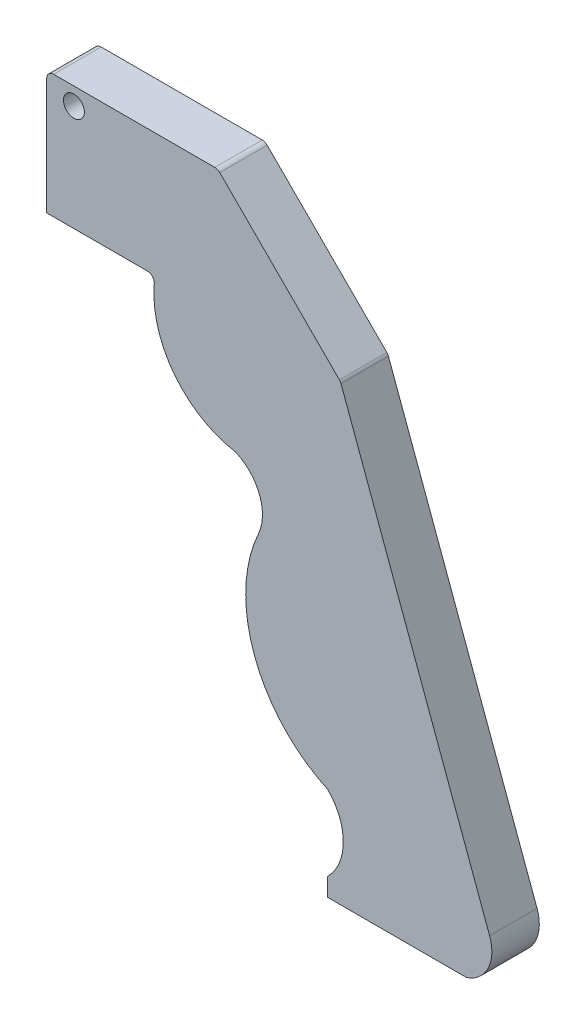
SolidWorks part; units mm, degrees
ref_plane "Front Plane" through (0, 0, 0) normal (0, 0, 1) x (1, 0, 0)
ref_plane "Top Plane" through (0, 0, 0) normal (0, 1, 0) x (1, 0, 0)
ref_plane "Right Plane" through (0, 0, 0) normal (1, 0, 0) x (0, 0, -1)
sketch "Croquis1" plane through (0, 0, 0) normal (0, 0, 1) x (1, 0, 0)
  line L0 (0, 0) -> (0, 17.7)
  line L1 (0, 17.7) -> (24.52, 17.7)
  line L2 (24.52, 17.7) -> (42.1128, 0.1072)
  line L3 (42.1128, 0.1072) -> (63.4977, -57.9922)
  line L4 (60.1681, -64.84) -> (40.2881, -64.84)
  line L5 (40.2881, -64.84) -> (40.2881, -62.22)
  line L6 (15.5596, 0) -> (0, 0)
  arc A0 (63.4977, -57.9922) -> (60.1681, -64.84) centre (58.5423, -59.8161) cw
  arc A1 (40.2881, -62.22) -> (40.2881, -51.4339) centre (34.895, -56.8269) ccw
  arc A2 (40.2881, -51.4339) -> (30.3996, -24.5683) centre (48.7766, -33.0568) cw
  arc A3 (30.3996, -24.5683) -> (27.0874, -16.1496) centre (24.5342, -22.015) ccw
  arc A4 (27.0874, -16.1496) -> (15.5596, 0) centre (29.3983, -2.3109) cw
  dimension "D1" = 24.52
  dimension "D2" = 24.88
  dimension "D3" = 61.91
  dimension "D4" = 19.88
  dimension "D5" = 2.62
  dimension "D6" = 15.5596
  dimension "D7" = 82.54
extrude "Saliente-Extruir1" add sketch "Croquis1" along normal mid plane 6.8
fillet "Redondeo1" radius 1 4 edges at (15.5596, 0, 0) (42.1128, 0.1072, 0) (24.52, 17.7, 0) (0, 17.7, 0)
sketch "Croquis2" plane through (0, 0, 3.4) normal (0, 0, 1) x (1, 0, 0)
  line L0 (24.1058, 17.7) -> (1, 17.7) construction
  line L1 (0, 16.7) -> (0, 0) construction
  circle A0 centre (3.9, 15.2) radius 1.5
  dimension "D1" = 3
  dimension "D2" = 2.5
  dimension "D3" = 3.9
extrude "Cortar-Extruir1" cut sketch "Croquis2" against normal through all
